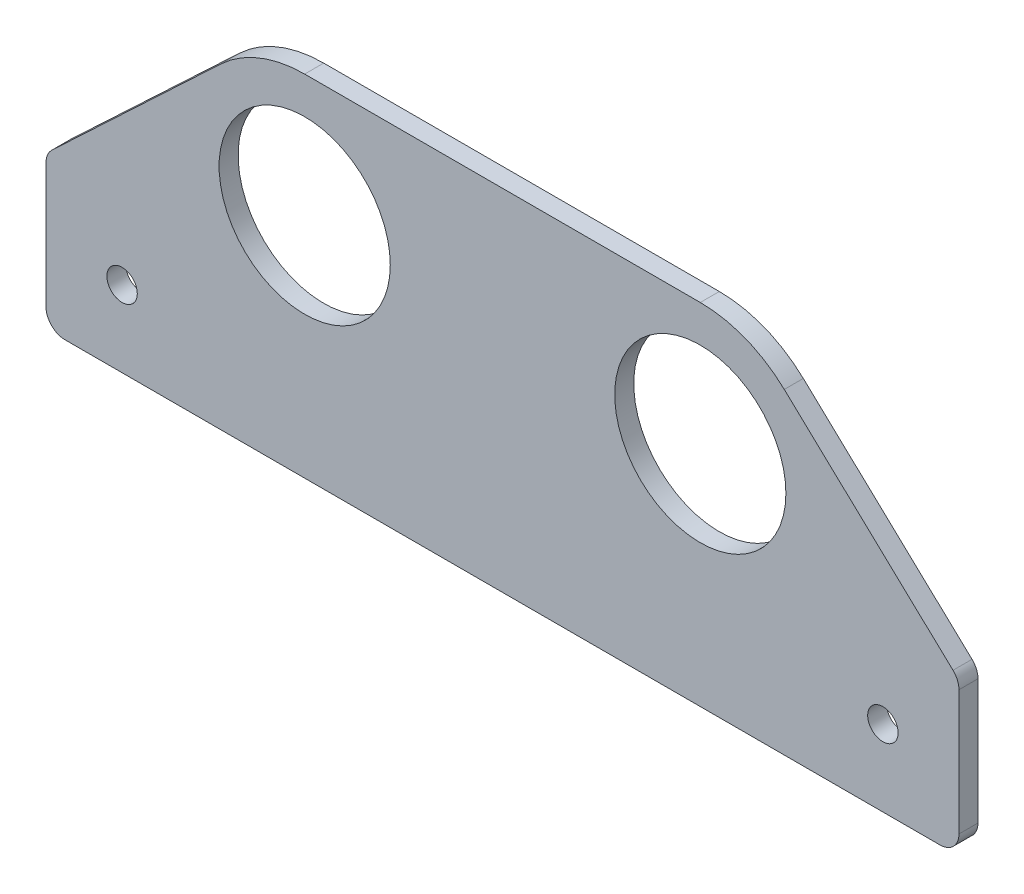
SolidWorks part; units mm, degrees
ref_plane "Front Plane" through (0, 0, 0) normal (0, 0, 1) x (1, 0, 0)
ref_plane "Top Plane" through (0, 0, 0) normal (0, 1, 0) x (1, 0, 0)
ref_plane "Right Plane" through (0, 0, 0) normal (1, 0, 0) x (0, 0, -1)
sketch "Sketch1" plane through (0, 0, 0) normal (0, 0, 1) x (1, 0, 0)
  line L0 (0, 0) -> (152.4, 0)
  line L1 (152.4, 0) -> (152.4, 25.4)
  line L3 (0, 0) -> (0, 25.4)
  line L4 (0, 25.4) -> (29.1631, 52.8595)
  line L5 (152.4, 25.4) -> (123.2369, 52.8595)
  line L6 (43.18, 58.42) -> (109.22, 58.42)
  line L8 (0, 0) -> (25.4, 0) construction
  line L9 (0, 0) -> (0, 25.4) construction
  line L10 (0, 25.4) -> (25.4, 25.4) construction
  line L11 (25.4, 0) -> (25.4, 25.4) construction
  line L12 (0, 0) -> (25.4, 25.4) construction
  line L13 (0, 25.4) -> (25.4, 0) construction
  line L14 (152.4, 0) -> (127, 0) construction
  line L15 (152.4, 0) -> (152.4, 25.4) construction
  line L16 (152.4, 25.4) -> (127, 25.4) construction
  line L17 (127, 0) -> (127, 25.4) construction
  line L18 (152.4, 0) -> (127, 25.4) construction
  line L19 (152.4, 25.4) -> (127, 0) construction
  circle A0 centre (43.18, 37.973) radius 20.447 construction
  circle A2 centre (109.22, 37.973) radius 20.447 construction
  arc A3 (29.1631, 52.8595) -> (43.18, 58.42) centre (43.18, 37.973) cw
  arc A4 (109.22, 58.42) -> (123.2369, 52.8595) centre (109.22, 37.973) cw
  circle A5 centre (43.18, 37.973) radius 14.2875
  circle A6 centre (109.22, 37.973) radius 14.2875
  circle A7 centre (12.7, 12.7) radius 2.54
  circle A8 centre (139.7, 12.7) radius 2.54
  point P17 (12.7, 12.7)
  point P22 (139.7, 12.7)
  dimension "D5" = 28.575
  dimension "D9" = 5.08
  dimension "D1" = 37.973
  dimension "D2" = 25.4
  dimension "D3" = 66.04
  dimension "D4" = 152.4
  dimension "D6" = 58.42
  dimension "D7" = 25.4
  dimension "D8" = 25.4
extrude "Boss-Extrude1" add sketch "Sketch1" along normal blind 3.175
fillet "Fillet1" radius 3.175 4 edges at (0, 25.4, 1.5875) (152.4, 0, 1.5875) (0, 0, 1.5875) (152.4, 25.4, 1.5875)
